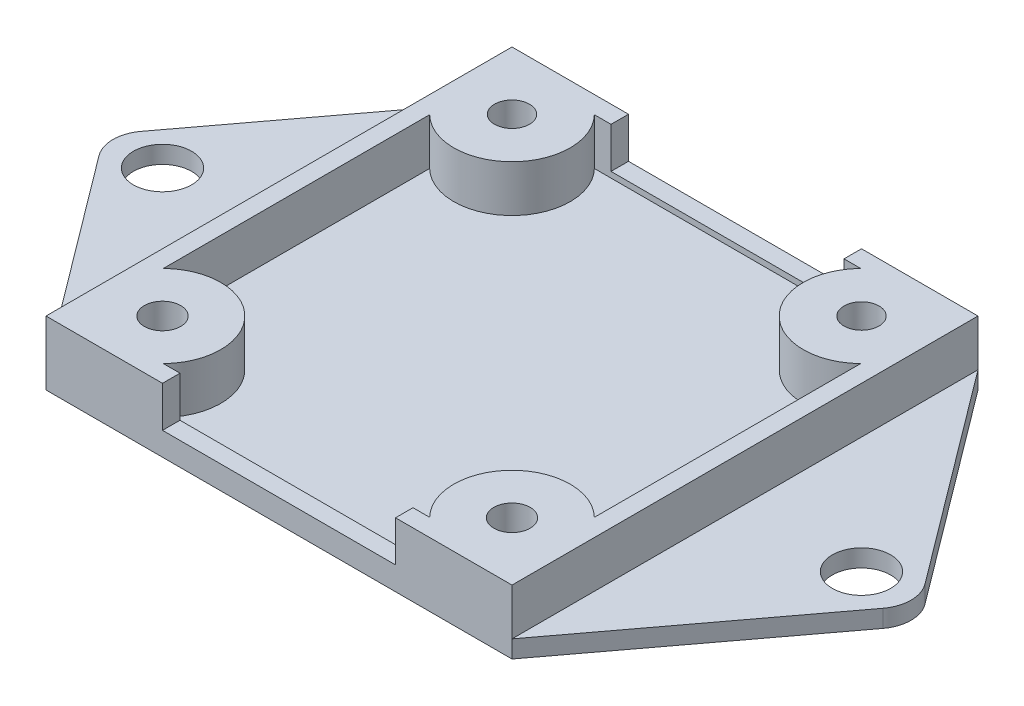
SolidWorks part; units mm, degrees
ref_plane "Front Plane" through (0, 0, 0) normal (0, 0, 1) x (1, 0, 0)
ref_plane "Top Plane" through (0, 0, 0) normal (0, 1, 0) x (1, 0, 0)
ref_plane "Right Plane" through (0, 0, 0) normal (1, 0, 0) x (0, 0, -1)
sketch "Sketch1" plane through (0, 0, 0) normal (0, 1, 0) x (1, 0, 0)
  line L0 (0, 20) -> (0, -20) construction
  line L1 (-20, 20) -> (20, 20)
  line L3 (-20, -20) -> (20, -20)
  line L5 (-20, 0) -> (20, 0) construction
  line L6 (-20, 20) -> (-35, 0)
  line L7 (-35, 0) -> (-20, -20)
  line L8 (20, 20) -> (35, 0)
  line L9 (35, 0) -> (20, -20)
  circle A1 centre (-15, 15) radius 1.5
  circle A2 centre (15, 15) radius 1.5
  circle A3 centre (15, -15) radius 1.5
  circle A4 centre (-15, -15) radius 1.5
  circle A5 centre (-30, 0) radius 2.5
  circle A6 centre (30, 0) radius 2.5
  point P0 (0, 0)
  point P9 (0, 0)
  point P12 (0, 0)
  dimension "D3" = 30
  dimension "D7" = 5
  dimension "D1" = 40
  dimension "D2" = 40
  dimension "D4" = 30
  dimension "D5" = 15
  dimension "D6" = 15
extrude "Boss-Extrude1" add sketch "Sketch1" along normal blind 1.5
sketch "Sketch2" plane through (0, 1.5, 0) normal (0, 1, 0) x (1, 0, 0)
  line L0 (-18.5, 11.4293) -> (-18.5, -11.4293)
  line L1 (-20, 20) -> (20, 20)
  line L2 (-20, 20) -> (-20, -20)
  line L3 (-20, -20) -> (20, -20)
  line L4 (20, 20) -> (20, -20)
  line L5 (0, 0) -> (6.5932, 0) construction
  line L7 (-11.4293, -18.5) -> (11.4293, -18.5)
  line L8 (18.5, 11.4293) -> (18.5, -11.4293)
  line L9 (-11.4293, 18.5) -> (11.4293, 18.5)
  line L10 (0, 0) -> (0, -8.2498) construction
  line L11 (-18.5, 18.5) -> (18.5, 18.5) construction
  line L12 (-16.0607, 16.0607) -> (16.1018, -16.1018) construction
  line L13 (-18.5, 18.5) -> (-18.5, -18.5) construction
  line L14 (-18.5, -18.5) -> (18.5, -18.5) construction
  line L15 (18.5, 18.5) -> (18.5, -18.5) construction
  line L16 (-16.1018, -16.1018) -> (16.0607, 16.0607) construction
  arc A1 (-18.5, 11.4293) -> (-11.4293, 18.5) centre (-15, 15) ccw
  circle A2 centre (-15, 15) radius 1.5
  circle A3 centre (15, -15) radius 1.5582
  arc A4 (18.5, 11.4293) -> (11.4293, 18.5) centre (15, 15) cw
  circle A5 centre (-15, -15) radius 1.5582
  arc A6 (18.5, -11.4293) -> (11.4293, -18.5) centre (15, -15) ccw
  circle A7 centre (15, 15) radius 1.5
  arc A8 (-18.5, -11.4293) -> (-11.4293, -18.5) centre (-15, -15) cw
  point P0 (0, 0)
  dimension "D2" = 30
  dimension "D4" = 3
  dimension "D3" = 30
  dimension "D1" = 1.5
extrude "Boss-Extrude2" add sketch "Sketch2" along normal blind 4
sketch "Sketch3" plane through (0, 0, 20) normal (0, 0, 1) x (1, 0, 0)
  line L0 (-20, 5.5) -> (20, 5.5) construction
  line L2 (-10, 2) -> (-10, 5.5)
  line L3 (-10, 5.5) -> (10, 5.5)
  line L4 (10, 2) -> (10, 5.5)
  line L5 (0, 0) -> (10, 5.5) construction
  line L6 (-10, 5.5) -> (0, 0) construction
  line L7 (-10, 2) -> (10, 2)
  point P0 (0, 0)
  dimension "D1" = 3.5
extrude "Cut-Extrude1" cut sketch "Sketch3" against normal blind 2
sketch "Sketch4" plane through (0, 0, -20) normal (0, 0, -1) x (-1, 0, 0)
  line L1 (-10, 5.5) -> (10, 5.5)
  line L2 (-10, 5.5) -> (-10, 2)
  line L3 (-10, 2) -> (10, 2)
  line L4 (10, 5.5) -> (10, 2)
extrude "Cut-Extrude2" cut sketch "Sketch4" against normal blind 2
fillet "Fillet1" radius 3 2 edges at (35, 0.75, 0) (-35, 0.75, 0)
